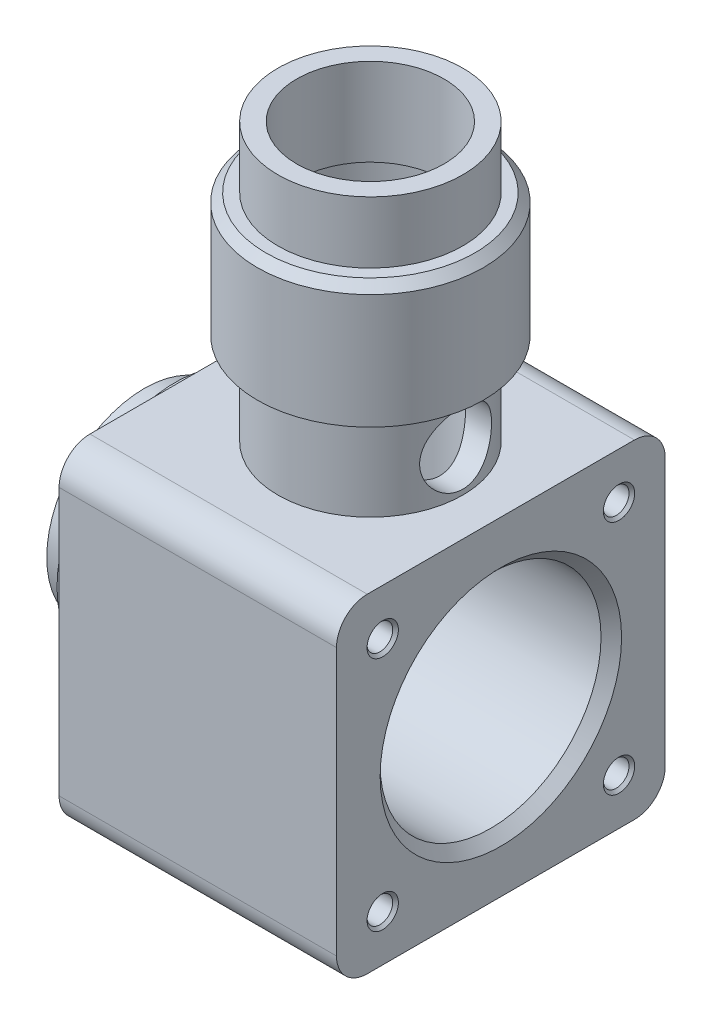
SolidWorks part; units mm, degrees
material "Сталь 12Х17 ГОСТ 5632-72"
ref_plane "Спереди" through (0, 0, 0) normal (0, 0, 1) x (1, 0, 0)
ref_plane "Сверху" through (0, 0, 0) normal (0, 1, 0) x (1, 0, 0)
ref_plane "Справа" through (0, 0, 0) normal (1, 0, 0) x (0, 0, -1)
sketch "Эскиз1" plane through (0, 0, 0) normal (0, 0, 1) x (1, 0, 0)
  line L0 (0, 0) -> (53.6101, 0) construction
  line L1 (0, -7) -> (11.6, -7)
  line L2 (0, -7) -> (0, -9.5)
  line L3 (0, -9.5) -> (3, -9.5)
  line L4 (3, -9.5) -> (3, -11.5)
  line L5 (3, -11.5) -> (4.2, -11.5)
  line L6 (4.2, -11.5) -> (4.2, -9.5)
  line L7 (4.2, -9.5) -> (7.7, -9.5)
  line L8 (7.7, -9.5) -> (7.7, -16)
  line L9 (7.7, -16) -> (34.7, -16)
  line L10 (34.7, -16) -> (34.7, -10.5)
  line L11 (34.7, -10.5) -> (11.6, -10.5) construction
  line L12 (11.6, -10.5) -> (11.6, -7) construction
  line L13 (11.6, -7) -> (11.6, 0)
  line L14 (11.6, 0) -> (34.7, 0)
  line L15 (34.7, 0) -> (34.7, -10.5)
  dimension "D1" = 11.6
  dimension "D2" = 7
  dimension "D3" = 9.5
  dimension "D4" = 3
  dimension "D5" = 2
  dimension "D6" = 1.2
  dimension "D7" = 16
  dimension "D8" = 27
  dimension "D9" = 3.5
  dimension "D10" = 5.5
revolve "Повернуть1" add sketch "Эскиз1" angle 360 about L0
sketch "Эскиз2" plane through (0, 0, 0) normal (0, 1, 0) x (1, 0, 0)
  circle A0 centre (22, 0) radius 9
  dimension "D1" = 18
  dimension "D2" = 22
extrude "Бобышка-Вытянуть1" add sketch "Эскиз2" along normal blind 25
sketch "Эскиз3" plane through (0, 25, 0) normal (0, 1, 0) x (1, 0, 0)
  circle A0 centre (22, 0) radius 11
  dimension "D1" = 22
extrude "Бобышка-Вытянуть2" add sketch "Эскиз3" along normal blind 12
cosmetic thread "Условное изображение резьбы1" parameters "D2"=20.344
sketch "Эскиз4" plane through (0, 37, 0) normal (0, 1, 0) x (1, 0, 0)
  circle A0 centre (22, 0) radius 9
  dimension "D1" = 18
extrude "Бобышка-Вытянуть3" add sketch "Эскиз4" along normal blind 6
sketch "Эскиз5" plane through (34.7, 0, 0) normal (1, 0, 0) x (0, 0, -1)
  circle A0 centre (0, 0) radius 10.75
  dimension "D1" = 21.5
extrude "Вырез-Вытянуть1" cut sketch "Эскиз5" against normal up to surface (23.1 mm away) up to face at (11.6, 0, 7)
sketch "Эскиз6" plane through (0, 43, 0) normal (0, 1, 0) x (1, 0, 0)
  circle A0 centre (22, 0) radius 8.5
  dimension "D1" = 17
extrude "Вырез-Вытянуть2" cut sketch "Эскиз6" against normal blind 7 from offset 8.5 offset against normal yes
sketch "Эскиз8" plane through (0, 27.5, 0) normal (0, 1, 0) x (1, 0, 0)
  circle A0 centre (22, 0) radius 6.75
  dimension "D1" = 13.5
extrude "Вырез-Вытянуть3" cut sketch "Эскиз8" against normal up to next
sketch "Эскиз9" plane through (0, 0, 0) normal (1, 0, 0) x (0, 0, -1)
  circle A0 centre (0, 20) radius 3.5
  dimension "D2" = 7
  dimension "D1" = 20
extrude "Вырез-Вытянуть4" cut sketch "Эскиз9" along normal through all
sketch "Эскиз10" plane through (34.7, 0, 0) normal (1, 0, 0) x (0, 0, -1)
  circle A0 centre (0, 0) radius 10.75 construction
  circle A1 centre (0, 0) radius 10.75
extrude "Бобышка-Вытянуть4" add sketch "Эскиз10" against normal blind 5.95
chamfer "Фаска1" distance 0.828 angle 45 1 edges at (22, 37, 11)
sketch "Эскиз12" plane through (34.7, 0, 0) normal (1, 0, 0) x (0, 0, -1)
  line L1 (-16, -16) -> (16, -16)
  line L2 (-16, -16) -> (-16, 16)
  line L3 (-16, 16) -> (16, 16)
  line L4 (16, -16) -> (16, 16)
  line L5 (-16, -16) -> (16, 16) construction
  line L6 (-16, 16) -> (16, -16) construction
  circle A0 centre (0, 0) radius 16 construction
  circle A3 centre (0, 0) radius 15
  circle A4 centre (0, 0) radius 15
  point P0 (0, 0)
  dimension "D1" = 1
extrude "Бобышка-Вытянуть5" add sketch "Эскиз12" against normal up to surface (27 mm away) up to face at (7.7, 0, 16)
sketch "Эскиз13" plane through (0, 16, 0) normal (0, 1, 0) x (1, 0, 0)
  circle A1 centre (22, 0) radius 6.75
  circle A2 centre (22, 0) radius 6.75
  dimension "D1" = 0
extrude "Вырез-Вытянуть5" cut sketch "Эскиз13" against normal up to next
sketch "Эскиз14" plane through (0, 43, 0) normal (0, 1, 0) x (1, 0, 0)
  circle A0 centre (22, 0) radius 7.172
  dimension "D1" = 14.344
extrude "Вырез-Вытянуть6" cut sketch "Эскиз14" against normal up to next
cosmetic thread "Условное изображение резьбы2" parameters "D2"=16
sketch "Эскиз18" plane through (28.75, 0, 0) normal (-1, 0, 0) x (0, 0, 1)
  circle A1 centre (0, 0) radius 10.75
  circle A2 centre (0, 0) radius 10.75
  dimension "D1" = 0
extrude "Вырез-Вытянуть11" cut sketch "Эскиз18" against normal up to next
sketch "Эскиз20" plane through (34.7, 0, 0) normal (1, 0, 0) x (0, 0, -1)
  line L1 (11.5, -11.5) -> (-11.5, -11.5) construction
  line L2 (11.5, -11.5) -> (11.5, 11.5) construction
  line L3 (11.5, 11.5) -> (-11.5, 11.5) construction
  line L4 (-11.5, -11.5) -> (-11.5, 11.5) construction
  line L5 (11.5, -11.5) -> (-11.5, 11.5) construction
  line L6 (11.5, 11.5) -> (-11.5, -11.5) construction
  point P0 (0, 0)
  dimension "D1" = 23
hole_wizard "Отверстие обработанное метчиком M3x0.51" positions "Трехмерный эскиз1" profile "Эскиз21" tap size "M3x0.5" standard "Ansi Metric"
sketch3d "Трехмерный эскиз1"
  point P0 (34.7, 11.5, 11.5)
  point P3 (34.7, -11.5, 11.5)
  point P6 (34.7, -11.5, -11.5)
  point P9 (34.7, 11.5, -11.5)
sketch "Эскиз21" plane through (34.7, 11.5, 11.5) normal (0, 1, 0) x (0, 0, -1)
  line L0 (0, 0) -> (0, 9.2511)
  line L1 (0, 9.2511) -> (1.25, 8.5)
  line L2 (1.25, 8.5) -> (1.25, 0.275)
  line L3 (1.25, 0.275) -> (1.525, 0)
  line L5 (1.525, 0) -> (0, 0)
  line L6 (-1.25, 0.275) -> (-1.525, 0) construction
  line L10 (0, 9.2511) -> (-1.25, 8.5) construction
  line L11 (0, -6.35) -> (0, 107.95) construction
  dimension "Диаметр сверла" = 2.5
  dimension "Глубина сверла" = 8.5
  dimension "Диаметр передней зенковки" = 3.05
  dimension "Угол передней зенковки" = 90
  dimension "Угол заточки сверла" = 118
cosmetic thread "Отверстие резьбы1" parameters "D1"=6, "D2"=3
cosmetic thread "Отверстие резьбы2" parameters "D1"=6, "D2"=3
cosmetic thread "Отверстие резьбы3" parameters "D1"=6, "D2"=3
cosmetic thread "Отверстие резьбы4" parameters "D1"=6, "D2"=3
fillet "Скругление1" radius 3 4 edges at (21.2, 16, -16) (21.2, -16, -16) (21.2, -16, 16) (21.2, 16, 16)
chamfer "Фаска2" distance 1 angle 45 1 edges at (34.7, 0, -10.75)
